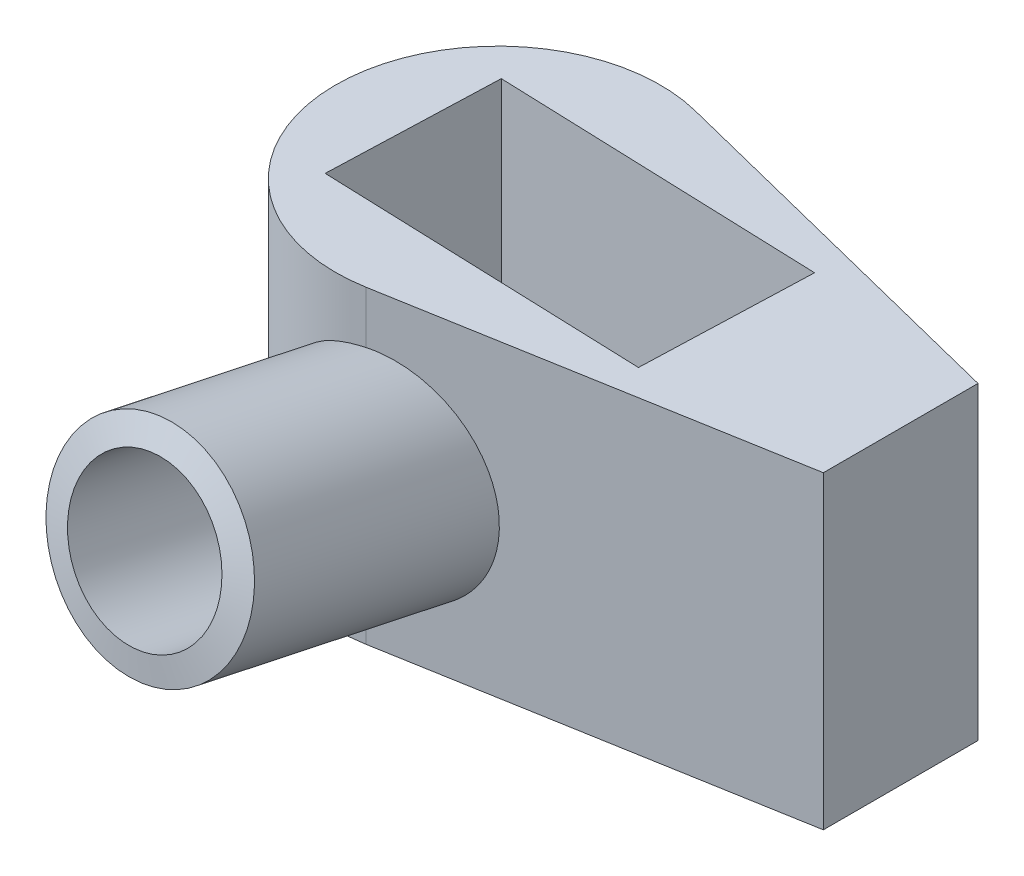
SolidWorks part; units mm, degrees
material "3.0205 (EN-AW 1200)"
ref_plane "Alzado" through (0, 0, 0) normal (0, 0, 1) x (1, 0, 0)
ref_plane "Planta" through (0, 0, 0) normal (0, 1, 0) x (1, 0, 0)
ref_plane "Vista lateral" through (0, 0, 0) normal (1, 0, 0) x (0, 0, -1)
sketch "Croquis1" plane through (0, 0, 0) normal (0, 1, 0) x (1, 0, 0)
  circle A0 centre (0, 0) radius 21
  dimension "D1" = 42
extrude "Saliente-Extruir1" add sketch "Croquis1" along normal blind 40
sketch "Croquis2" plane through (0, 0, 0) normal (0, 1, 0) x (1, 0, 0)
  line L0 (53.9751, 8.111) -> (53.9751, -11.889)
  line L1 (53.9751, -11.889) -> (3.6138, -20.6867)
  line L2 (53.9751, 8.111) -> (5.1095, 20.3689)
  circle A0 centre (0, 0) radius 21 construction
  arc A1 (3.6138, -20.6867) -> (5.1095, 20.3689) centre (0, 0) ccw
  dimension "D1" = 20
extrude "Saliente-Extruir2" add sketch "Croquis2" along normal blind 40
sketch "Croquis3" plane through (5.1095, 0, -20.3689) normal (0.2433, 0, -0.9699) x (-0.9699, 0, -0.2433)
  line L0 (0, 40) -> (0, 0) construction
  circle A0 centre (0, 20) radius 10
  circle A1 centre (0, 20) radius 13.5
  dimension "D1" = 20
  dimension "D2" = 27
extrude "Saliente-Extruir3" add sketch "Croquis3" against normal up to surface (2.5338 mm away)
ref_plane "Plano1" through (5.1, 0, 0) normal (1, 0, 0) x (0, 0, -1)
sketch "Croquis4" plane through (5.1, 0, 0) normal (1, 0, 0) x (0, 0, -1)
  line L9 (-24.6165, 20.6635) -> (-48.2898, 25.7004)
  line L10 (-1.889, 40) -> (-1.889, 0)
  line L11 (-11.889, 40) -> (8.111, 40) construction
  line L12 (-11.889, 0) -> (8.111, 0) construction
  line L13 (-24.6165, 10.6635) -> (-17.7768, 9.2083)
  line L14 (-17.7768, 9.2083) -> (-17.7768, 5.7083)
  line L15 (-52.8165, 16.6635) -> (-52.8165, 13.1635)
  line L16 (-24.6165, 10.6635) -> (-52.8165, 16.6635)
  line L17 (-52.8165, 7.1635) -> (-52.8165, 13.1635)
  line L18 (-24.6165, 7.1635) -> (-52.8165, 7.1635)
  line L19 (-17.7768, 5.7083) -> (-52.8165, 13.1635)
sketch "Croquis7" plane through (0, 0, 0) normal (0, -1, 0) x (1, 0, 0)
  circle A0 centre (0, 0) radius 6
  circle A1 centre (0, 0) radius 8.2273
  dimension "D1" = 16.4545
  dimension "D2" = 12
extrude "Cortar-Extruir6" cut sketch "Croquis7" against normal blind 6
sketch "Croquis8" plane through (0, 0, 0) normal (0, -1, 0) x (1, 0, 0)
  circle A0 centre (0, 0) radius 6
extrude "Cortar-Extruir7" cut sketch "Croquis8" against normal through all
sketch "Croquis10" plane through (0, 40, 0) normal (0, 1, 0) x (1, 0, 0)
  line L0 (-11.3782, 0.4245) -> (30.6218, -1.0623)
  line L1 (-10.9888, 11.4245) -> (31.0112, 9.9377)
  line L2 (-10.9888, 11.4245) -> (-11.7676, -10.5755)
  line L3 (31.0112, 9.9377) -> (30.2324, -12.0623)
  line L4 (-11.7676, -10.5755) -> (30.2324, -12.0623)
  line L5 (37.4945, -5.951) -> (37.4945, -5.9648)
  line L7 (53.9751, -1.889) -> (-20.9861, 0.7646)
  line L8 (53.9751, -11.889) -> (53.9751, 8.111) construction
  arc A0 (5.1095, 20.3689) -> (3.6138, -20.6867) centre (0, 0) ccw construction
  point P7 (16.4945, -0.5622)
  circle M7 centre (0, 0) radius 6
  dimension "D1" = 11
  dimension "D2" = 42
extrude "Cortar-Extruir8" cut sketch "Croquis10" against normal blind 25 contours L2 L4 L3 L0 M7 | L3 L1 L2 L0 M7
sketch "Croquis12" plane through (0, 15, 0) normal (0, 1, 0) x (1, 0, 0)
  circle A0 centre (0, 0) radius 9.55
  dimension "D1" = 19.1
extrude "Cortar-Extruir9" cut sketch "Croquis12" against normal blind 5.5
sketch "Croquis15" plane through (53.9751, 0, 0) normal (1, 0, 0) x (0, 0, -1)
revolve "Revolución3" add sketch "Croquis4" angle 360 about L9
sketch "Croquis17" plane through (0, 40, 0) normal (0, 1, 0) x (1, 0, 0)
  line L0 (5.1095, 20.3689) -> (5.1095, 31.6806)
  line L1 (5.1095, 31.6806) -> (-13.6883, 31.6806)
  line L2 (-13.6883, 31.6806) -> (-13.6883, 15.9257)
  arc A0 (5.1095, 20.3689) -> (-13.6883, 15.9257) centre (0, 0) ccw
extrude "Cortar-Extruir10" cut sketch "Croquis17" against normal through all contours A0 L2 L1 L0
